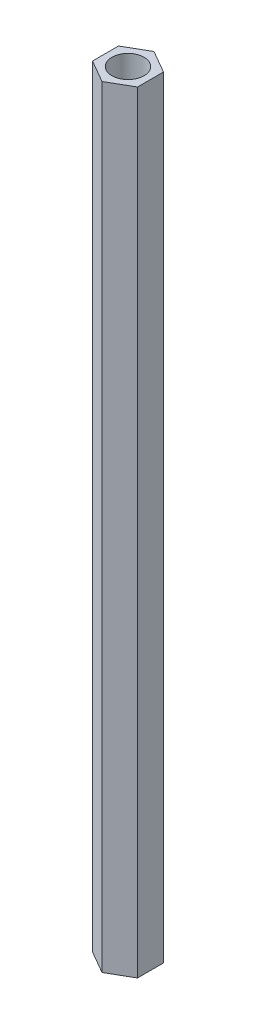
SolidWorks part; units mm, degrees
ref_plane "Front Plane" through (0, 0, 0) normal (0, 0, 1) x (1, 0, 0)
ref_plane "Top Plane" through (0, 0, 0) normal (0, 1, 0) x (1, 0, 0)
ref_plane "Right Plane" through (0, 0, 0) normal (1, 0, 0) x (0, 0, -1)
sketch "Sketch1" plane through (0, 0, 0) normal (0, 1, 0) x (1, 0, 0)
  line L1 (0, 2.0207) -> (-1.75, 1.0104)
  line L2 (-1.75, 1.0104) -> (-1.75, -1.0104)
  line L3 (-1.75, -1.0104) -> (0, -2.0207)
  line L4 (0, -2.0207) -> (1.75, -1.0104)
  line L5 (1.75, -1.0104) -> (1.75, 1.0104)
  line L6 (1.75, 1.0104) -> (0, 2.0207)
  circle A0 centre (0, 0) radius 1.75 construction
  dimension "D1" = 3.5
extrude "Boss-Extrude1" add sketch "Sketch1" along normal blind 60
hole_wizard "M3x0.5 Tapped Hole1" positions "Sketch2" profile "Sketch3" tap size "M3x0.5" standard "ANSI Metric"
sketch "Sketch2" plane through (0, 60, 0) normal (0, 1, 0) x (1, 0, 0)
  point P0 (0, 0)
sketch "Sketch3" plane through (0, 60, 0) normal (1, 0, 0) x (0, 0, 1)
  line L0 (0, 0) -> (0, 10.7511)
  line L1 (0, 10.7511) -> (1.25, 10)
  line L2 (1.25, 10) -> (1.25, 0)
  line L5 (1.25, 0) -> (0, 0)
  line L10 (0, 10.7511) -> (-1.25, 10) construction
  line L11 (0, -6.35) -> (0, 107.95) construction
  dimension "Tap Drill Dia." = 2.5
  dimension "Tap Drill Depth" = 10
  dimension "Drill Angle" = 118
hole_wizard "M3x0.5 Tapped Hole2" positions "Sketch4" profile "Sketch5" tap size "M3x0.5" standard "ANSI Metric"
sketch "Sketch4" plane through (0, 0, 0) normal (0, -1, 0) x (-1, 0, 0)
  point P0 (0, 0)
sketch "Sketch5" plane through (0, 0, 0) normal (1, 0, 0) x (0, 0, -1)
  line L0 (0, 0) -> (0, 10.7511)
  line L1 (0, 10.7511) -> (1.25, 10)
  line L2 (1.25, 10) -> (1.25, 0)
  line L5 (1.25, 0) -> (0, 0)
  line L10 (0, 10.7511) -> (-1.25, 10) construction
  line L11 (0, -6.35) -> (0, 107.95) construction
  dimension "Tap Drill Dia." = 2.5
  dimension "Tap Drill Depth" = 10
  dimension "Drill Angle" = 118
